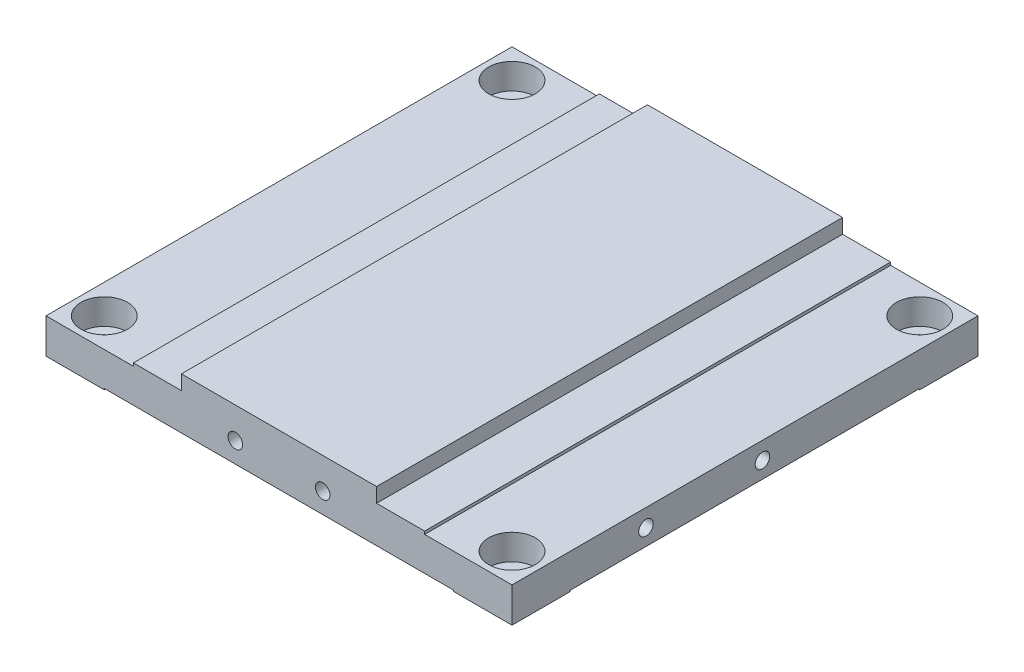
SolidWorks part; units mm, degrees
material "6061"
ref_plane "前视" through (0, 0, 0) normal (0, 0, 1) x (1, 0, 0)
ref_plane "上视" through (0, 0, 0) normal (0, 1, 0) x (1, 0, 0)
ref_plane "右视" through (0, 0, 0) normal (1, 0, 0) x (0, 0, -1)
sketch "草图1" plane through (0, 0, 0) normal (0, 1, 0) x (1, 0, 0)
  line L1 (-40, -40) -> (40, -40)
  line L2 (-40, -40) -> (-40, 40)
  line L3 (-40, 40) -> (40, 40)
  line L4 (40, -40) -> (40, 40)
  line L5 (-40, -40) -> (40, 40) construction
  line L6 (-40, 40) -> (40, -40) construction
  point P0 (0, 0)
  dimension "D1" = 80
extrude "凸台-拉伸1" add sketch "草图1" along normal blind 9
sketch "草图2" plane through (0, 0, 40) normal (0, 0, 1) x (1, 0, 0)
  line L0 (0, 9) -> (0, 0) construction
  line L1 (-40, 9) -> (40, 9) construction
  line L2 (16.75, 9) -> (16.75, 6.5)
  line L3 (-40, 9) -> (-16.75, 9)
  line L4 (-40, 9) -> (-40, 6.5)
  line L5 (-40, 6.5) -> (-16.75, 6.5)
  line L6 (-16.75, 9) -> (-16.75, 6.5)
  line L7 (40, 6.5) -> (16.75, 6.5)
  line L8 (40, 9) -> (40, 6.5)
  line L9 (40, 9) -> (16.75, 9)
  dimension "D1" = 33.5
  dimension "D2" = 2.5
extrude "切除-拉伸1" cut sketch "草图2" against normal through all
sketch "草图10" plane through (0, 0, 40) normal (0, 0, 1) x (1, 0, 0)
  line L0 (0, 9) -> (0, -7.5757) construction
  line L1 (-16.75, 9) -> (16.75, 9) construction
  line L2 (25, 6.5) -> (25, 6)
  line L3 (-40, 6.5) -> (-25, 6.5)
  line L4 (-40, 6.5) -> (-40, 6)
  line L5 (-40, 6) -> (-25, 6)
  line L6 (-25, 6.5) -> (-25, 6)
  line L7 (40, 6) -> (25, 6)
  line L8 (40, 6.5) -> (40, 6)
  line L9 (40, 6.5) -> (25, 6.5)
  dimension "D1" = 0.5
  dimension "D2" = 50
extrude "切除-拉伸3" cut sketch "草图10" against normal through all
hole_wizard "打孔尺寸根据内六角圆柱头螺钉的类型1" positions "草图4" profile "草图3" counterbore size "M4" standard "Gb" end condition through all
sketch "草图4" plane through (-39.3356, 6, 5.2805) normal (0, 1, 0) x (1, 0, 0)
  line L0 (39.3356, 40) -> (39.3356, 5.2805) construction
  line L2 (39.3356, 5.2805) -> (79.3356, 5.2805) construction
  line L3 (79.3356, 45.2805) -> (79.3356, -34.7195) construction
  point P0 (4.3356, 40.2805)
  point P12 (74.3356, 40.2805)
  point P13 (74.3356, -29.7195)
  point P14 (4.3356, -29.7195)
  dimension "D1" = 70
  dimension "D2" = 70
sketch "草图3" plane through (-35, 6, -35) normal (1, 0, 0) x (0, 0, 1)
  line L0 (0, 0) -> (0, 6)
  line L1 (0, 6) -> (2.25, 6)
  line L3 (2.25, 6) -> (2.25, 4.4)
  line L4 (2.25, 4.4) -> (4, 4.4)
  line L5 (4, 4.4) -> (4, 0)
  line L7 (4, 0) -> (0, 0)
  line L11 (0, -6.35) -> (0, 107.95) construction
  dimension "通孔孔直径" = 4.5
  dimension "通孔孔深度" = 6
  dimension "柱形沉头孔直径" = 8
  dimension "柱形沉头孔深度" = 4.4
hole_wizard "M3 螺纹孔1" positions "草图7" profile "草图6" tap size "M3" standard "Gb"
sketch "草图7" plane through (-40, 0, 0) normal (-1, 0, 0) x (0, 0, 1)
  line L0 (-40, 0) -> (40, 0) construction
  line L1 (40, 6) -> (40, 0) construction
  point P0 (7, 3)
  point P2 (-13, 3)
  dimension "D1" = 3
  dimension "D2" = 20
  dimension "D3" = 33
sketch "草图6" plane through (-40, 3, 7) normal (0, 1, 0) x (0, 0, 1)
  line L0 (0, 0) -> (0, 8.2511)
  line L1 (0, 8.2511) -> (1.25, 7.5)
  line L2 (1.25, 7.5) -> (1.25, 0)
  line L5 (1.25, 0) -> (0, 0)
  line L10 (0, 8.2511) -> (-1.25, 7.5) construction
  line L11 (0, -6.35) -> (0, 107.95) construction
  dimension "螺纹孔钻头直径" = 2.5
  dimension "螺纹孔钻头深度" = 7.5
  dimension "导头角度" = 118
cosmetic thread "孔螺蚊线1" parameters "D1"=6, "D2"=3
cosmetic thread "孔螺蚊线2" parameters "D1"=6, "D2"=3
hole_wizard "M3 螺纹孔2" positions "草图9" profile "草图8" tap size "M3" standard "Gb"
sketch "草图9" plane through (40, 0, 0) normal (1, 0, 0) x (0, 0, -1)
  line L0 (-40, 6) -> (-40, 0) construction
  point P0 (3, 3)
  point P2 (-17, 3)
  dimension "D1" = 23
  dimension "D2" = 20
sketch "草图8" plane through (40, 3, -3) normal (0, 1, 0) x (0, 0, -1)
  line L0 (0, 0) -> (0, 8.2511)
  line L1 (0, 8.2511) -> (1.25, 7.5)
  line L2 (1.25, 7.5) -> (1.25, 0)
  line L5 (1.25, 0) -> (0, 0)
  line L10 (0, 8.2511) -> (-1.25, 7.5) construction
  line L11 (0, -6.35) -> (0, 107.95) construction
  dimension "螺纹孔钻头直径" = 2.5
  dimension "螺纹孔钻头深度" = 7.5
  dimension "导头角度" = 118
cosmetic thread "孔螺蚊线3" parameters "D1"=6, "D2"=3
cosmetic thread "孔螺蚊线4" parameters "D1"=6, "D2"=3
sketch "草图5" plane through (0, 0, 0) normal (0, -1, 0) x (1, 0, 0)
  line L0 (0, 40) -> (0, 0) construction
  line L1 (-40, 40) -> (40, 40) construction
  line L2 (0, 0) -> (-40, 0) construction
  line L3 (-40, -40) -> (-40, 40) construction
  line L4 (30, 40) -> (30, 30)
  line L5 (-40, 40) -> (-30, 40)
  line L6 (-40, 40) -> (-40, 30)
  line L7 (-40, 30) -> (-30, 30)
  line L8 (-30, 40) -> (-30, 30)
  line L9 (40, 30) -> (30, 30)
  line L10 (40, 40) -> (40, 30)
  line L11 (40, 40) -> (30, 40)
  line L12 (40, -40) -> (30, -40)
  line L13 (40, -40) -> (40, -30)
  line L14 (40, -30) -> (30, -30)
  line L15 (30, -40) -> (30, -30)
  line L16 (-30, -40) -> (-30, -30)
  line L17 (-40, -30) -> (-30, -30)
  line L18 (-40, -40) -> (-40, -30)
  line L19 (-40, -40) -> (-30, -40)
  dimension "D1" = 10
extrude "切除-拉伸2" cut sketch "草图5" against normal blind 0.2 flip side to cut
hole_wizard "M3 螺纹孔3" positions "草图12" profile "草图11" tap size "M3" standard "Gb"
sketch "草图12" plane through (0, 0, 40) normal (0, 0, 1) x (1, 0, 0)
  line L0 (0, 9) -> (0, -7.8375) construction
  line L1 (-16.75, 9) -> (16.75, 9) construction
  line L4 (30, 0) -> (40, 0) construction
  point P0 (-7.5, 3.7)
  point P11 (7.5, 3.7)
  dimension "D1" = 15
  dimension "D2" = 3.7
sketch "草图11" plane through (-7.5, 3.7, 40) normal (1, 0, 0) x (0, -1, 0)
  line L0 (0, 0) -> (0, 8.2511)
  line L1 (0, 8.2511) -> (1.25, 7.5)
  line L2 (1.25, 7.5) -> (1.25, 0)
  line L5 (1.25, 0) -> (0, 0)
  line L10 (0, 8.2511) -> (-1.25, 7.5) construction
  line L11 (0, -6.35) -> (0, 107.95) construction
  dimension "螺纹孔钻头直径" = 2.5
  dimension "螺纹孔钻头深度" = 7.5
  dimension "导头角度" = 118
cosmetic thread "孔螺蚊线5" parameters "D1"=6, "D2"=3
cosmetic thread "孔螺蚊线6" parameters "D1"=6, "D2"=3
mirror "镜向1" about plane through (0, 0, 0) normal (0, 0, 1) of "M3 螺纹孔3"
